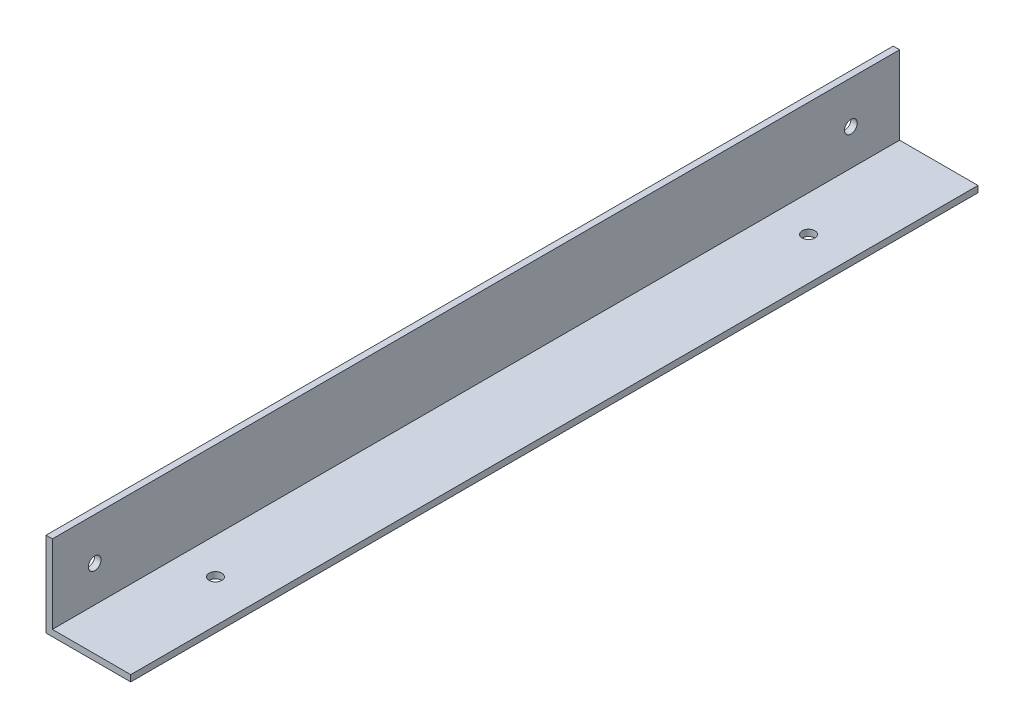
SolidWorks part; units mm, degrees
ref_plane "Plan de face" through (0, 0, 0) normal (0, 0, 1) x (1, 0, 0)
ref_plane "Plan de dessus" through (0, 0, 0) normal (0, 1, 0) x (1, 0, 0)
ref_plane "Plan de droite" through (0, 0, 0) normal (1, 0, 0) x (0, 0, -1)
sketch "Esquisse1" plane through (0, 0, 0) normal (0, 0, 1) x (1, 0, 0)
  line L0 (-18.1135, 1.8189) -> (-18.1135, -18.1811)
  line L1 (-18.1135, -18.1811) -> (1.8865, -18.1811)
  line L2 (1.8865, -18.1811) -> (1.8865, -16.6811)
  line L3 (1.8865, -16.6811) -> (-16.6135, -16.6811)
  line L4 (-16.6135, -16.6811) -> (-16.6135, 1.8189)
  line L5 (-16.6135, 1.8189) -> (-18.1135, 1.8189)
  dimension "D1" = 1.5
  dimension "D2" = 1.5
  dimension "D3" = 20
  dimension "D4" = 20
extrude "Extrusion1" add sketch "Esquisse1" along normal blind 200
sketch "Esquisse2" plane through (0, -16.6811, 0) normal (0, 1, 0) x (-1, 0, 0)
  line L0 (18.1135, 200) -> (-1.8865, 200) construction
  line L1 (-1.8865, 200) -> (16.6135, 200) construction
  line L2 (8.1135, 30) -> (8.1135, 170) construction
  line L3 (-1.8865, 200) -> (-1.8865, 0) construction
  line L4 (-1.8865, 0) -> (16.6135, 0) construction
  circle A0 centre (8.1135, 170) radius 1.5
  circle A1 centre (8.1135, 30) radius 1.5
  point P2 (8.1135, 200)
  dimension "D2" = 30
  dimension "D1" = 10
  dimension "D3" = 30
sketch "Esquisse3" plane through (-16.6135, 0, 0) normal (1, 0, 0) x (0, 0, -1)
  line L0 (-190, -8.1811) -> (-11.5, -8.1811) construction
  line L1 (-200, -16.6811) -> (-200, 1.8189) construction
  line L2 (0, -16.6811) -> (0, 1.8189) construction
  line L3 (-200, 1.8189) -> (0, 1.8189) construction
  circle A0 centre (-11.5, -8.1811) radius 1.5
  circle A1 centre (-190, -8.1811) radius 1.5
  dimension "D1" = 11.5
  dimension "D2" = 10
  dimension "D3" = 10
extrude "Extrusion3" cut sketch "Esquisse3" against normal blind 150
extrude "Extrusion4" cut sketch "Esquisse2" against normal blind 100
